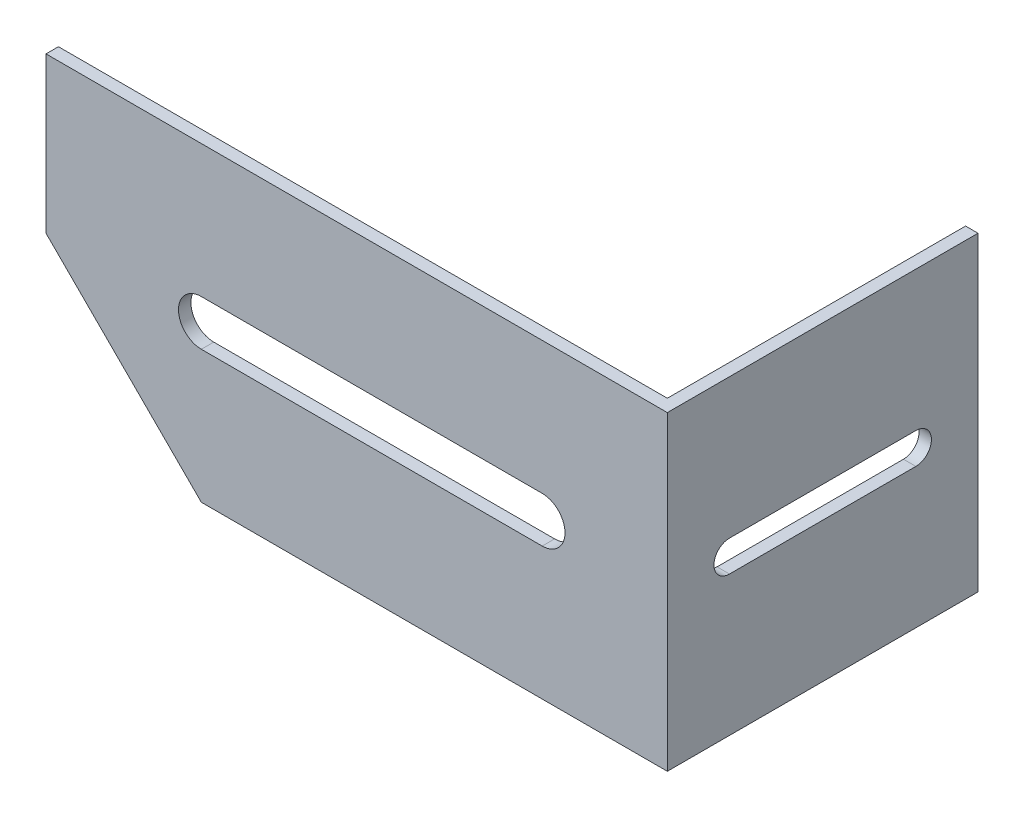
SolidWorks part; units mm, degrees
ref_plane "Front Plane" through (0, 0, 0) normal (0, 0, 1) x (1, 0, 0)
ref_plane "Top Plane" through (0, 0, 0) normal (0, 1, 0) x (1, 0, 0)
ref_plane "Right Plane" through (0, 0, 0) normal (1, 0, 0) x (0, 0, -1)
sketch "Sketch1" plane through (0, 0, 0) normal (0, 0, 1) x (1, 0, 0)
  line L0 (-75, 0) -> (-100, 25)
  line L1 (0, 0) -> (-100, 0)
  line L2 (0, 0) -> (0, 50)
  line L3 (0, 50) -> (-100, 50)
  line L4 (-100, 0) -> (-100, 50)
  line L5 (-75, 25) -> (-20.1422, 25) construction
  line L6 (-75, 28.673) -> (-20.1422, 28.673)
  line L7 (-75, 21.327) -> (-20.1422, 21.327)
  arc A0 (-75, 28.673) -> (-75, 21.327) centre (-75, 25) ccw
  arc A1 (-20.1422, 21.327) -> (-20.1422, 28.673) centre (-20.1422, 25) ccw
  point P9 (-47.5711, 25)
  point P14 (0, 0)
  point P15 (-20.1422, 25)
  dimension "D1" = 100
  dimension "D2" = 50
  dimension "D3" = 75
  dimension "D4" = 25
  dimension "D5" = 7.346
extrude "Boss-Extrude1" add sketch "Sketch1" along normal blind 50 contours L4 L0 L1 L2 L3 A1 L7 A0 L6
shell "Shell2" thickness 2
sketch "Sketch2" plane through (0, 0, 0) normal (1, 0, 0) x (0, 0, -1)
  line L0 (-40, 25) -> (-10, 25) construction
  line L1 (-40, 27.5) -> (-10, 27.5)
  line L2 (-40, 22.5) -> (-10, 22.5)
  line L3 (-50, 50) -> (0, 50) construction
  line L4 (0, 0) -> (0, 50) construction
  line L5 (-50, 0) -> (-50, 50) construction
  arc A0 (-40, 27.5) -> (-40, 22.5) centre (-40, 25) ccw
  arc A1 (-10, 22.5) -> (-10, 27.5) centre (-10, 25) ccw
  point P2 (-25, 25)
  dimension "D1" = 25
  dimension "D2" = 10
  dimension "D3" = 10
  dimension "D4" = 5
extrude "Cut-Extrude1" cut sketch "Sketch2" against normal blind 60
